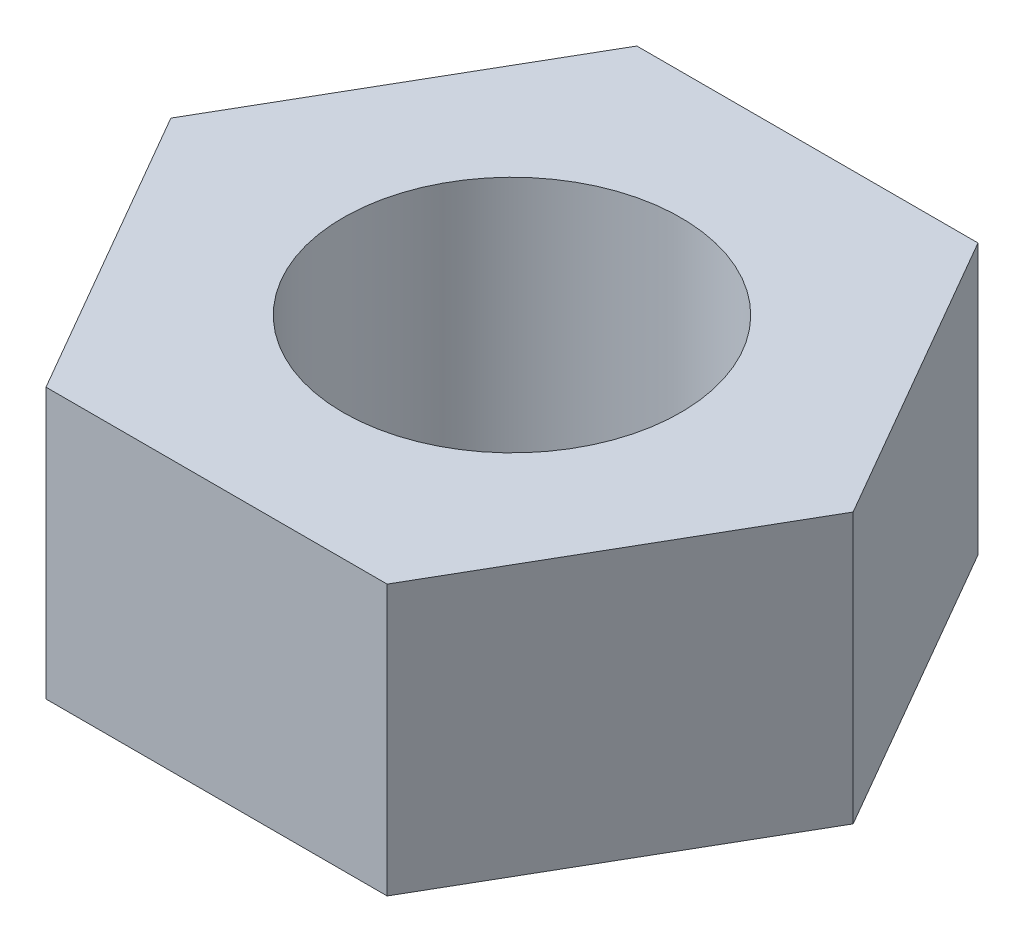
SolidWorks part; units mm, degrees
material "Alloy Steel"
ref_plane "Front" through (0, 0, 0) normal (0, 0, 1) x (1, 0, 0)
ref_plane "Top" through (0, 0, 0) normal (0, 1, 0) x (1, 0, 0)
ref_plane "Right" through (0, 0, 0) normal (1, 0, 0) x (0, 0, -1)
sketch "Sketch1" plane through (0, 0, 0) normal (0, 1, 0) x (1, 0, 0)
  line L1 (2.0207, -3.5) -> (4.0415, 0)
  line L2 (4.0415, 0) -> (2.0207, 3.5)
  line L3 (2.0207, 3.5) -> (-2.0207, 3.5)
  line L4 (-2.0207, 3.5) -> (-4.0415, 0)
  line L5 (-4.0415, 0) -> (-2.0207, -3.5)
  line L6 (-2.0207, -3.5) -> (2.0207, -3.5)
  circle A0 centre (0, 0) radius 3.5 construction
  circle A1 centre (0, 0) radius 2
  dimension "D2" = 4
  dimension "D1" = 7
extrude "Boss-Extrude1" add sketch "Sketch1" along normal blind 3.2
